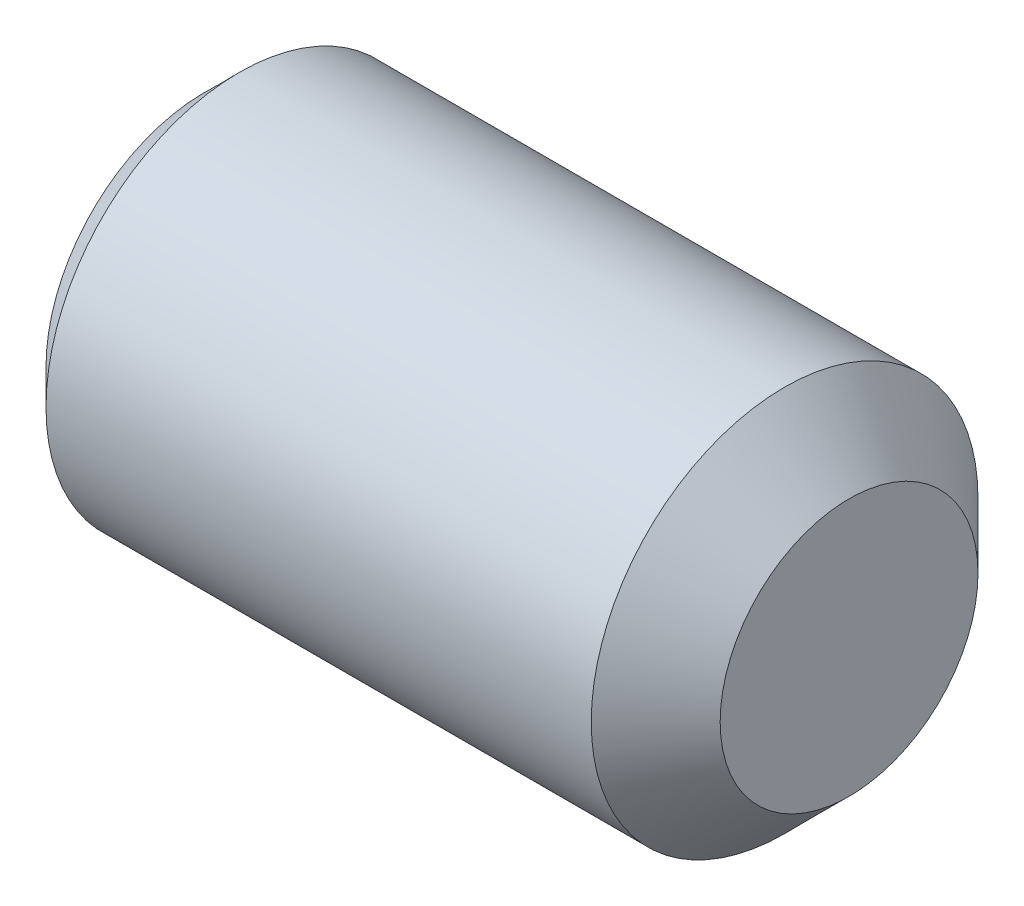
SolidWorks part; units mm, degrees
ref_plane "Front Plane" through (0, 0, 0) normal (0, 0, 1) x (1, 0, 0)
ref_plane "Top Plane" through (0, 0, 0) normal (0, 1, 0) x (1, 0, 0)
ref_plane "Right Plane" through (0, 0, 0) normal (1, 0, 0) x (0, 0, -1)
ref_plane "Plane1" through (0, 0, 0) normal (0, 0, -1) x (-1, 0, 0)
sketch "Sketch1" plane through (0, 0, 0) normal (0, 0, -1) x (-1, 0, 0)
  line L0 (-5, 1.5) -> (-5, 0)
  line L1 (-5, 0) -> (0, 0)
  line L2 (0, 0) -> (0, 1.5)
  line L3 (0, 1.5) -> (-5, 1.5)
  line L4 (-5, 0) -> (0, 0) construction
revolve "Revolve1" add sketch "Sketch1" angle 360 about L4
sketch "Sketch2" plane through (0, 0, 0) normal (-1, 0, 0) x (0, 0, 1)
  line L0 (-0.75, -0.433) -> (0, -0.866)
  line L1 (0, -0.866) -> (0.75, -0.433)
  line L2 (0.75, -0.433) -> (0.75, 0.433)
  line L3 (0.75, 0.433) -> (0, 0.866)
  line L4 (0, 0.866) -> (-0.75, 0.433)
  line L5 (-0.75, 0.433) -> (-0.75, -0.433)
extrude "Cut-Extrude1" cut sketch "Sketch2" against normal blind 1.2
chamfer "Chamfer1" distance 0.2706 angle 45 1 edges at (0, 0, 1.5)
chamfer "Chamfer2" distance 0.5 angle 45 1 edges at (5, 0, 1.5)
